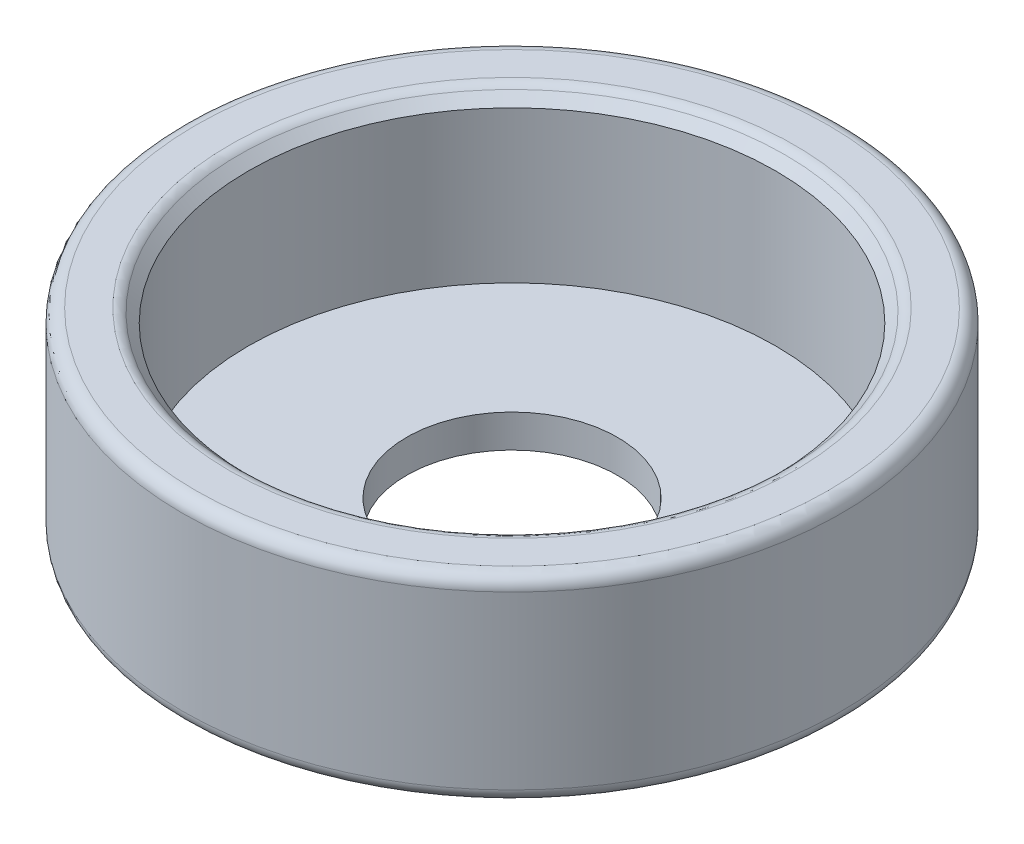
SolidWorks part; units mm, degrees
ref_plane "Front Plane" through (0, 0, 0) normal (0, 0, 1) x (1, 0, 0)
ref_plane "Top Plane" through (0, 0, 0) normal (0, 1, 0) x (1, 0, 0)
ref_plane "Right Plane" through (0, 0, 0) normal (1, 0, 0) x (0, 0, -1)
sketch "Sketch1" plane through (0, 0, 0) normal (0, 1, 0) x (1, 0, 0)
  circle A0 centre (0, 0) radius 5
  circle A1 centre (0, 0) radius 1.6
  dimension "D1" = 10
  dimension "D2" = 3.2
extrude "Boss-Extrude1" add sketch "Sketch1" along normal blind 3
sketch "Sketch2" plane through (0, 3, 0) normal (0, 1, 0) x (1, 0, 0)
  circle A0 centre (0, 0) radius 4
  dimension "D1" = 8
extrude "Cut-Extrude1" cut sketch "Sketch2" against normal blind 2.5
chamfer "Chamfer1" distance 0.2 angle 45 1 edges at (0, 3, 4)
fillet "Fillet2" radius 0.2 3 edges at (0, 3, 5) (0, 3, 4.2) (0, 0, 5)
